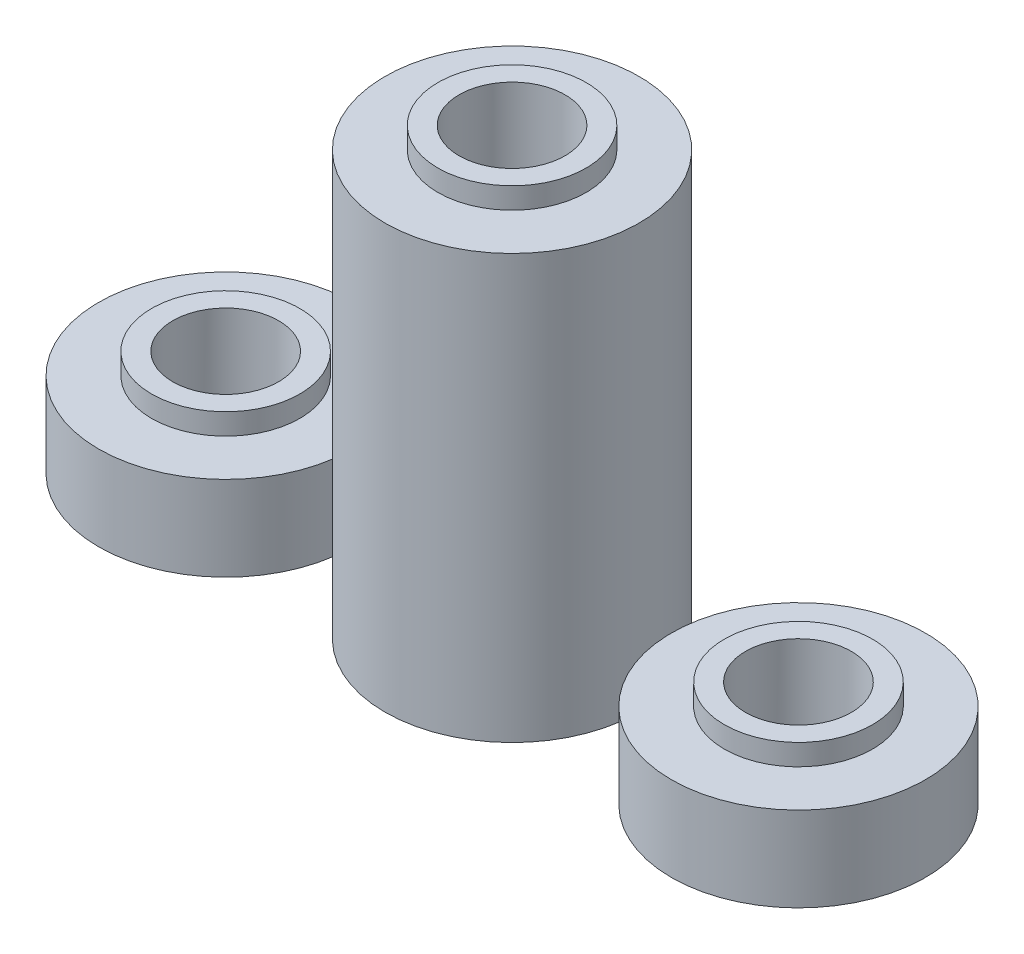
SolidWorks part; units mm, degrees
ref_plane "Alzado" through (0, 0, 0) normal (0, 0, 1) x (1, 0, 0)
ref_plane "Planta" through (0, 0, 0) normal (0, 1, 0) x (1, 0, 0)
ref_plane "Vista lateral" through (0, 0, 0) normal (1, 0, 0) x (0, 0, -1)
sketch "Croquis1" plane through (0, 0, 0) normal (0, 1, 0) x (1, 0, 0)
  circle A0 centre (0, 0) radius 6
  dimension "D1" = 12
extrude "Saliente-Extruir1" add sketch "Croquis1" along normal blind 20
sketch "Croquis2" plane through (0, 20, 0) normal (0, 1, 0) x (1, 0, 0)
  circle A0 centre (0, 0) radius 2.5
  dimension "D1" = 5
extrude "Cortar-Extruir1" cut sketch "Croquis2" against normal blind 20
sketch "Croquis3" plane through (0, 20, 0) normal (0, 1, 0) x (1, 0, 0)
  line L0 (0, 0) -> (-2.2409, -1.1083) construction
  line L1 (-2.2409, -1.1083) -> (-3.1373, -1.5516) construction
  circle A0 centre (0, 0) radius 2.5
  circle A1 centre (0, 0) radius 3.5
  circle A2 centre (0, 0) radius 2.5 construction
  dimension "D1" = 1
extrude "Saliente-Extruir2" add sketch "Croquis3" along normal blind 1
sketch "Croquis4" plane through (0, 0, 0) normal (0, -1, 0) x (1, 0, 0)
  circle A0 centre (0, 0) radius 4.5
  dimension "D1" = 9
extrude "Cortar-Extruir2" cut sketch "Croquis4" against normal blind 5
sketch "Croquis5" plane through (0, 0, 0) normal (0, 1, 0) x (1, 0, 0)
  line L0 (0, 0) -> (-13.522, 0) construction
  circle A0 centre (-13.522, 0) radius 6
  point P4 (-13.522, 0)
  dimension "D1" = 12
extrude "Saliente-Extruir3" add sketch "Croquis5" along normal blind 4 separate body
sketch "Croquis6" plane through (0, 4, 0) normal (0, 1, 0) x (1, 0, 0)
  circle A0 centre (-13.522, 0) radius 2.5
  dimension "D1" = 5
extrude "Cortar-Extruir3" cut sketch "Croquis6" against normal blind 4
sketch "Croquis7" plane through (0, 4, 0) normal (0, 1, 0) x (1, 0, 0)
  line L0 (-13.522, 0) -> (-15.9753, -0.4809) construction
  line L1 (-15.9753, -0.4809) -> (-16.9566, -0.6733) construction
  circle A0 centre (-13.522, 0) radius 2.5
  circle A1 centre (-13.522, 0) radius 3.5
  circle A4 centre (-13.522, 0) radius 2.5 construction
  dimension "D1" = 1
extrude "Saliente-Extruir4" add sketch "Croquis7" along normal blind 1
sketch "Croquis8" plane through (0, 0, 0) normal (0, -1, 0) x (1, 0, 0)
  circle A1 centre (-13.522, 0) radius 3.5
  circle A2 centre (-13.522, 0) radius 3.5
  circle A3 centre (-13.522, 0) radius 2.5
  circle A4 centre (-13.522, 0) radius 2.5
  dimension "D1" = 0
  dimension "D2" = 0
extrude "Cortar-Extruir4" cut sketch "Croquis8" against normal blind 1
mirror "Simetría2" about plane through (0, 0, 0) normal (1, 0, 0) of bodies 108
